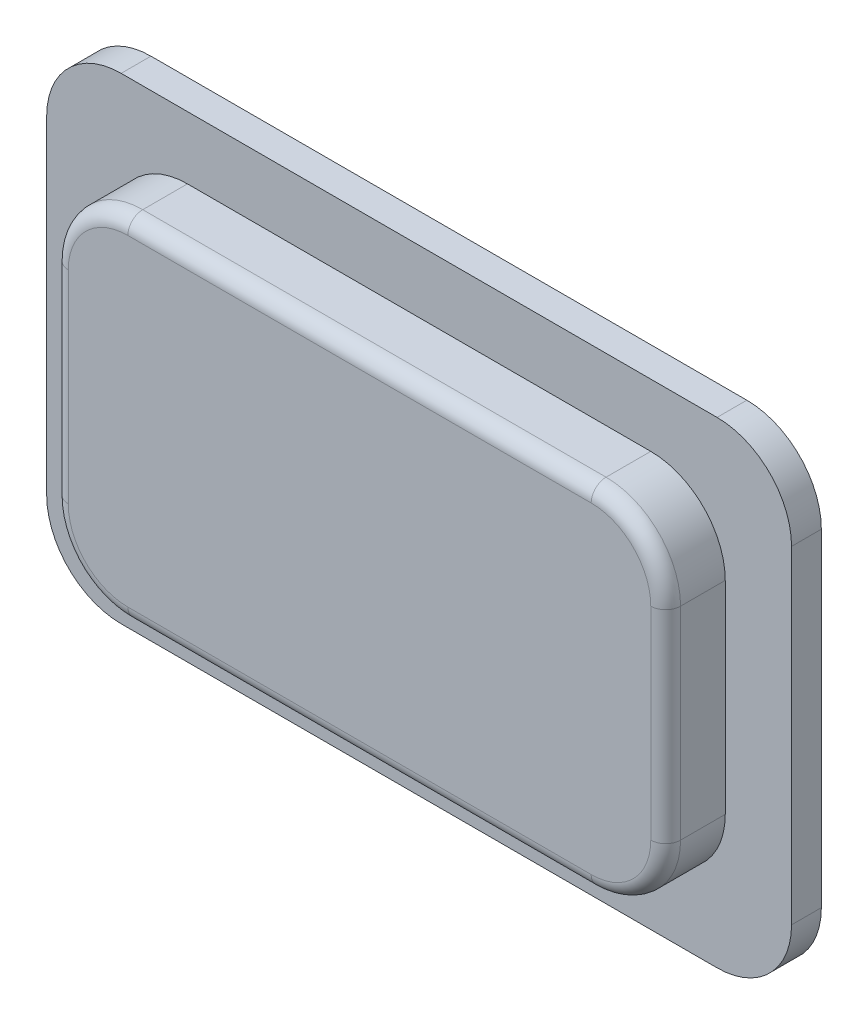
SolidWorks part; units mm, degrees
ref_plane "Front Plane" through (0, 0, 0) normal (0, 0, 1) x (1, 0, 0)
ref_plane "Top Plane" through (0, 0, 0) normal (0, 1, 0) x (1, 0, 0)
ref_plane "Right Plane" through (0, 0, 0) normal (1, 0, 0) x (0, 0, -1)
sketch "Sketch1" plane through (0, 0, 0) normal (0, 0, 1) x (1, 0, 0)
  line L1 (-12.5, -8) -> (12.5, -8)
  line L2 (-12.5, -8) -> (-12.5, 8)
  line L3 (-12.5, 8) -> (12.5, 8)
  line L4 (12.5, -8) -> (12.5, 8)
  line L5 (-12.5, -8) -> (12.5, 8) construction
  line L6 (-12.5, 8) -> (12.5, -8) construction
  point P0 (0, 0)
  dimension "D1" = 16
  dimension "D2" = 25
extrude "Boss-Extrude1" add sketch "Sketch1" against normal blind 1
sketch "Sketch2" plane through (0, 0, 0) normal (0, 0, 1) x (1, 0, 0)
  line L1 (-10.275, 5.9) -> (10.275, 5.9)
  line L2 (-10.275, 5.9) -> (-10.275, -5.9)
  line L3 (-10.275, -5.9) -> (10.275, -5.9)
  line L4 (10.275, 5.9) -> (10.275, -5.9)
  line L5 (-10.275, 5.9) -> (10.275, -5.9) construction
  line L6 (-10.275, -5.9) -> (10.275, 5.9) construction
  point P0 (0, 0)
  dimension "D1" = 11.8
  dimension "D2" = 20.55
extrude "Boss-Extrude2" add sketch "Sketch2" along normal blind 2
fillet "Fillet1" radius 2.5 8 edges at (-12.5, -8, -0.5) (-12.5, 8, -0.5) (12.5, 8, -0.5) (12.5, -8, -0.5) (10.275, 5.9, 1) (-10.275, 5.9, 1) (-10.275, -5.9, 1) (10.275, -5.9, 1)
fillet "Fillet2" radius 0.5 8 edges at (9.5428, -5.1678, 2) (0, -5.9, 2) (-9.5428, -5.1678, 2) (-10.275, 0, 2) (-9.5428, 5.1678, 2) (0, 5.9, 2) (9.5428, 5.1678, 2) (10.275, 0, 2)
